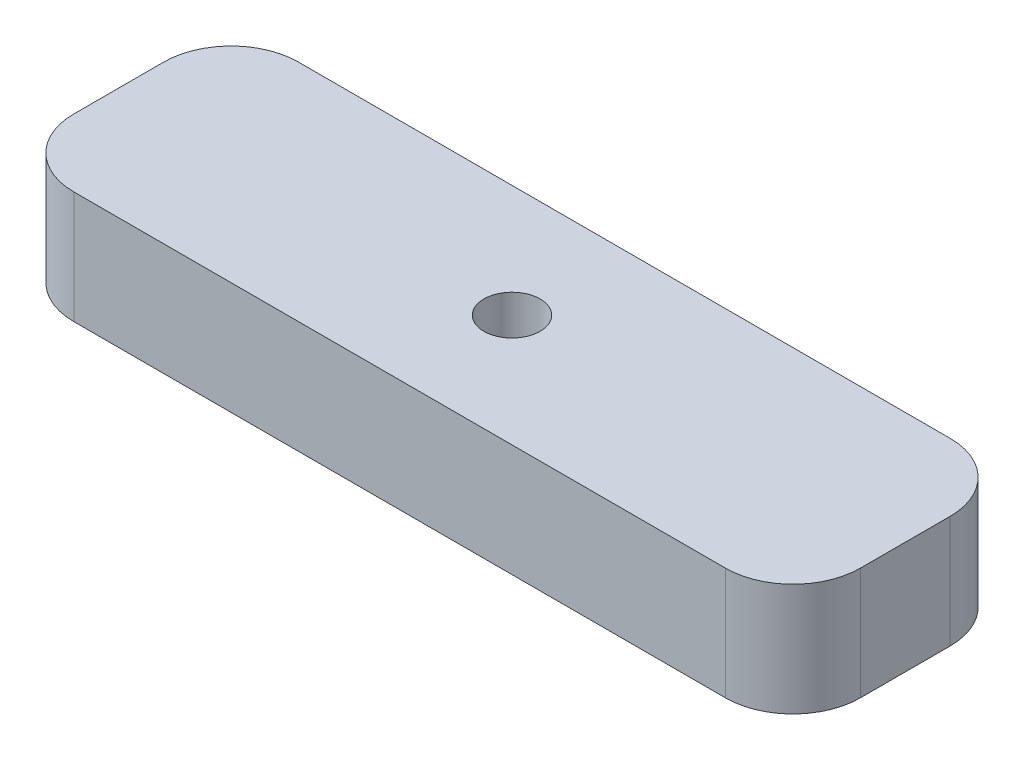
SolidWorks part; units mm, degrees
material "Медь"
ref_plane "Спереди" through (0, 0, 0) normal (0, 0, 1) x (1, 0, 0)
ref_plane "Сверху" through (0, 0, 0) normal (0, 1, 0) x (1, 0, 0)
ref_plane "Справа" through (0, 0, 0) normal (1, 0, 0) x (0, 0, -1)
sketch "Эскиз1" plane through (0, 0, 0) normal (0, 1, 0) x (1, 0, 0)
  line L1 (-17.5, -5) -> (17.5, -5)
  line L2 (-17.5, -5) -> (-17.5, 5)
  line L3 (-17.5, 5) -> (17.5, 5)
  line L4 (17.5, -5) -> (17.5, 5)
  line L5 (-17.5, -5) -> (17.5, 5) construction
  line L6 (-17.5, 5) -> (17.5, -5) construction
  circle A0 centre (0, 0) radius 1.25
  point P0 (0, 0)
  dimension "D1" = 10
  dimension "D2" = 35
extrude "Бобышка-Вытянуть1" add sketch "Эскиз1" along normal blind 5
fillet "Скругление1" radius 3 4 edges at (-17.5, 2.5, 5) (-17.5, 2.5, -5) (17.5, 2.5, 5) (17.5, 2.5, -5)
